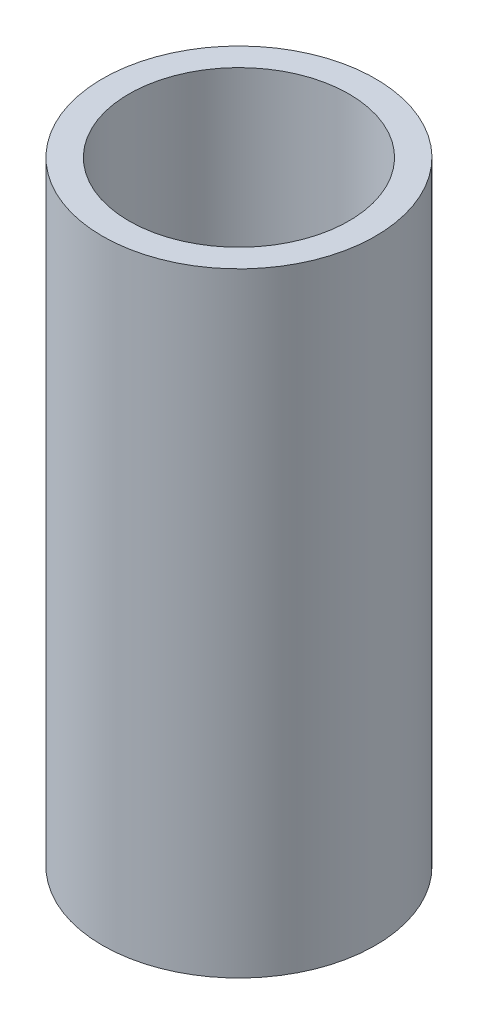
SolidWorks part; units mm, degrees
ref_plane "Front Plane" through (0, 0, 0) normal (0, 0, 1) x (1, 0, 0)
ref_plane "Top Plane" through (0, 0, 0) normal (0, 1, 0) x (1, 0, 0)
ref_plane "Right Plane" through (0, 0, 0) normal (1, 0, 0) x (0, 0, -1)
sketch "Sketch1" plane through (0, 0, 0) normal (0, 1, 0) x (1, 0, 0)
  circle A0 centre (0, 0) radius 6.45
  circle A1 centre (0, 0) radius 8
  dimension "D1" = 12.9
  dimension "D2" = 16
extrude "Boss-Extrude1" add sketch "Sketch1" along normal blind 36
